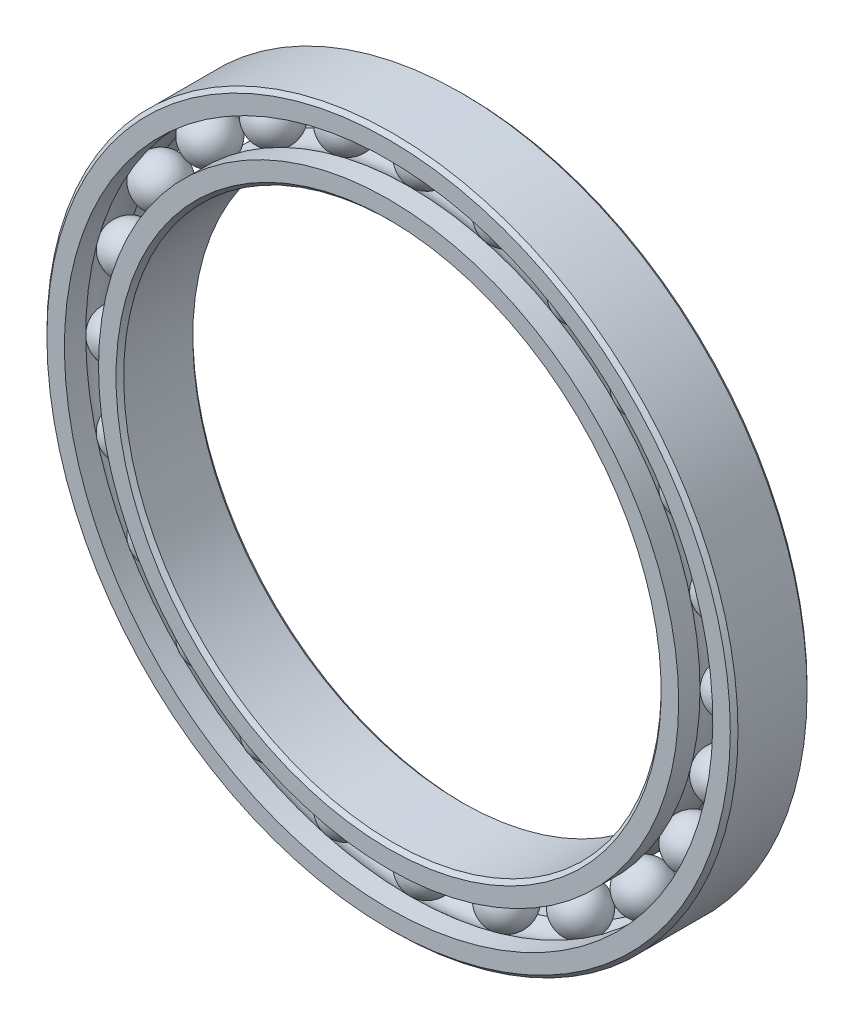
SolidWorks part; units mm, degrees
ref_plane "Front Plane" through (0, 0, 0) normal (0, 0, 1) x (1, 0, 0)
ref_plane "Top Plane" through (0, 0, 0) normal (0, 1, 0) x (1, 0, 0)
ref_plane "Right Plane" through (0, 0, 0) normal (1, 0, 0) x (0, 0, -1)
sketch "Sketch1" plane through (0, 0, 0) normal (0, 0, 1) x (1, 0, 0)
  circle A0 centre (0, 0) radius 45
  circle A1 centre (0, 0) radius 35
  dimension "OD" = 90
  dimension "ID" = 70
  dimension "For Shaft Diameter" = 70
  dimension "For Housing ID" = 90
sketch "Sketch5" plane through (0, 0, 0) normal (1, 0, 0) x (0, 0, -1)
  line L0 (-5, 0) -> (5, 0) construction
  line L1 (0, 45) -> (0, -45) construction
  line L2 (4.5, 45) -> (-4.5, 45)
  line L3 (-4.5, 45) -> (-5, 44.5)
  line L4 (-5, 44.5) -> (-5, 42.2222)
  line L5 (-5, 42.2222) -> (-2.2222, 42.2222)
  line L6 (5, 42.2222) -> (2.2222, 42.2222)
  line L7 (5, 44.5) -> (5, 42.2222)
  line L8 (4.5, 45) -> (5, 44.5)
  line L9 (0, 45) -> (0, 40) construction
  line L10 (0, 40) -> (0, 35) construction
  line L11 (-3.1427, 40) -> (-5, 40) construction
  line L12 (3.8808, 37.8032) -> (4.2618, 37.8032) construction
  line L13 (-3.8808, 37.8032) -> (-4.2618, 37.8032) construction
  line L14 (-3.8808, 37.8032) -> (-3.8808, 42.1968) construction
  line L15 (-3.8808, 42.1968) -> (-4.2618, 42.1968) construction
  line L16 (-4.2618, 37.8032) -> (-4.2618, 42.1968) construction
  line L17 (-3.8808, 37.8032) -> (-4.2618, 42.1968) construction
  line L18 (-3.8808, 42.1968) -> (-4.2618, 37.8032) construction
  line L19 (4.2618, 37.8032) -> (4.2618, 42.1968) construction
  line L20 (3.8808, 42.1968) -> (4.2618, 42.1968) construction
  line L21 (3.8808, 37.8032) -> (3.8808, 42.1968) construction
  line L22 (0, 45) -> (0, -45) construction
  arc A0 (-2.2222, 42.2222) -> (2.2222, 42.2222) centre (0, 40) cw
  circle A1 centre (0, 40) radius 3.1427 construction
  point P14 (0, 35)
  point P15 (-4.0713, 40)
  dimension "D1" = 45
  dimension "D2" = 0.5
  dimension "D3" = 4.4444
  dimension "D4" = 2.2222
  dimension "D5" = 0.381
  dimension "D6" = 0.0254
  dimension "Width" = 10
sketch "Sketch6" plane through (0, 0, 0) normal (1, 0, 0) x (0, 0, -1)
  line L0 (4.5, 45) -> (5, 44.5) construction
  line L1 (5, 44.5) -> (5, 42.2222) construction
  line L2 (5, 42.2222) -> (2.2222, 42.2222) construction
  line L3 (-5, 42.2222) -> (-2.2222, 42.2222) construction
  line L4 (-5, 44.5) -> (-5, 42.2222) construction
  line L5 (-4.5, 45) -> (-5, 44.5) construction
  line L6 (4.5, 45) -> (-4.5, 45) construction
  line L7 (4.5, 45) -> (5, 44.5)
  line L8 (5, 44.5) -> (5, 42.2222)
  line L9 (5, 42.2222) -> (2.2222, 42.2222)
  line L10 (-5, 42.2222) -> (-2.2222, 42.2222)
  line L11 (-5, 44.5) -> (-5, 42.2222)
  line L12 (-4.5, 45) -> (-5, 44.5)
  line L13 (4.5, 45) -> (-4.5, 45)
  arc A0 (2.2222, 42.2222) -> (-2.2222, 42.2222) centre (0, 40) ccw construction
  arc A1 (2.2222, 42.2222) -> (-2.2222, 42.2222) centre (0, 40) ccw
revolve "Revolve5" add sketch "Sketch6" angle 360 about L0
sketch "Sketch3" plane through (0, 0, 0) normal (1, 0, 0) x (0, 0, -1)
  line L0 (-5, 37.7778) -> (-2.2222, 37.7778)
  line L1 (0, 45) -> (0, -45) construction
  line L2 (-5, 44.5) -> (-5, 42.2222) construction
  line L3 (-5, 37.7778) -> (-5, 35.5)
  line L4 (-4.5, 45) -> (-5, 44.5) construction
  line L5 (-5, 35.5) -> (-4.5, 35)
  line L6 (-4.5, 35) -> (4.5, 35)
  line L8 (4.5, 35) -> (5, 35.5)
  line L10 (5, 35.5) -> (5, 37.7778)
  line L11 (5, 37.7778) -> (2.2222, 37.7778)
  line L12 (4.5, 45) -> (4.5, -45) construction
  line L13 (4.5, 45) -> (5, 44.5) construction
  line L14 (5, -44.5) -> (5, 44.5) construction
  arc A0 (2.2222, 42.2222) -> (-2.2222, 42.2222) centre (0, 40) ccw construction
  arc A1 (2.2222, 37.7778) -> (-2.2222, 37.7778) centre (0, 40) cw
revolve "Revolve3" add sketch "Sketch3" angle 360 about L0
sketch "Sketch4" plane through (0, 0, 0) normal (1, 0, 0) x (0, 0, -1)
  line L0 (-3.1427, 40) -> (3.1427, 40)
  arc A2 (-3.1427, 40) -> (3.1427, 40) centre (0, 40) cw
  arc A3 (2.2222, 42.2222) -> (-2.2222, 42.2222) centre (0, 40) ccw construction
revolve "Revolve4" add sketch "Sketch4" angle 360 about L0
pattern_circular "CirPattern1" count 24 over 360 about axis through (0, 0, 0) along (0, 0, 1) of bodies 104
equation "\"D2@Sketch5\" = \"Width@Sketch5\" * .05"
equation "\"D3@Sketch5\" = \"Width@Sketch5\" / 2.25"
equation "\"D4@Sketch5\"=((\"OD@Sketch1\"-\"ID@Sketch1\")/2)/4.5"
